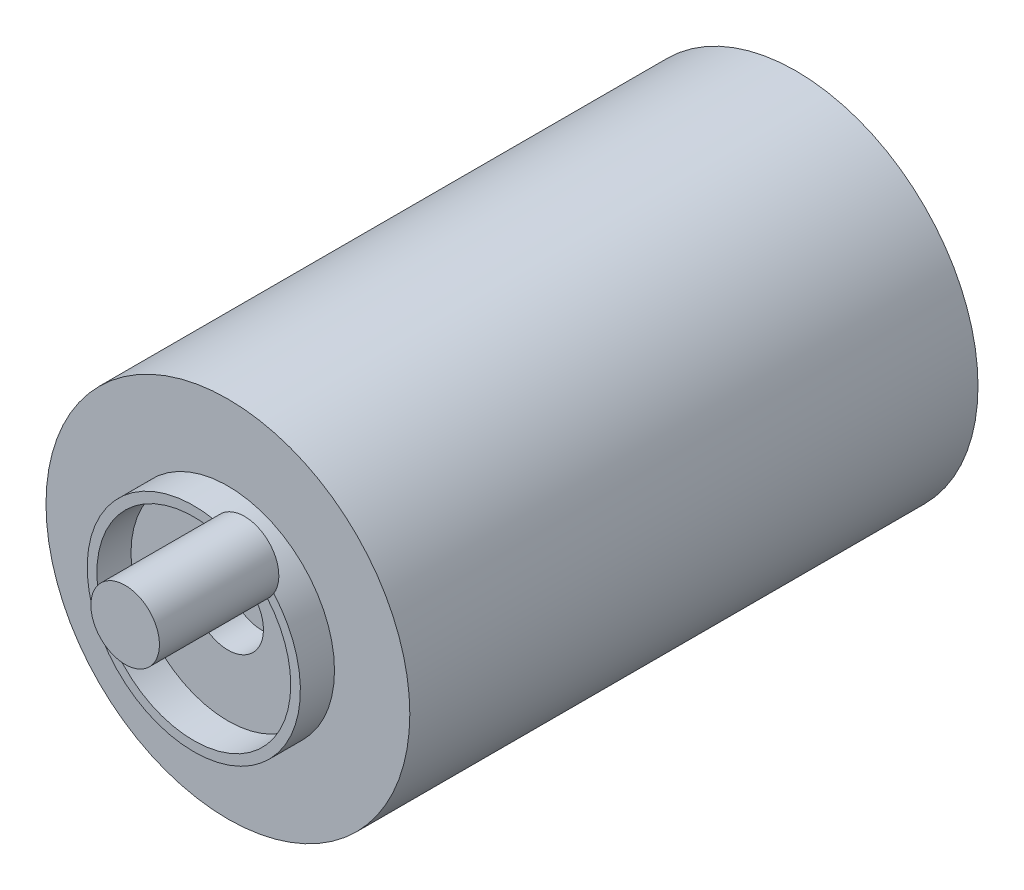
SolidWorks part; units mm, degrees
ref_plane "Front" through (0, 0, 0) normal (0, 0, 1) x (1, 0, 0)
ref_plane "Top" through (0, 0, 0) normal (0, 1, 0) x (1, 0, 0)
ref_plane "Right" through (0, 0, 0) normal (1, 0, 0) x (0, 0, -1)
sketch "Sketch1" plane through (0, 0, 0) normal (0, 0, 1) x (1, 0, 0)
  circle A0 centre (0, 0) radius 64
  point P3 (0, 0)
  dimension "D1" = 128
extrude "Boss-Extrude1" add sketch "Sketch1" along normal blind 10 and the other way blind 189.9
sketch "Sketch3" plane through (0, 0, 10) normal (0, 0, 1) x (1, 0, 0)
  circle A0 centre (0, 0) radius 37.5
  dimension "D1" = 75
extrude "Boss-Extrude2" add sketch "Sketch3" along normal blind 12 contours A0
sketch "Sketch4" plane through (0, 0, 22) normal (0, 0, 1) x (1, 0, 0)
  circle A0 centre (0, 0) radius 34.1038
  point P3 (0, 0)
extrude "Cut-Extrude1" cut sketch "Sketch4" against normal blind 12
sketch "Sketch5" plane through (0, 0, 10) normal (0, 0, 1) x (1, 0, 0)
  circle A0 centre (0, 0) radius 12.5
  dimension "D1" = 25
extrude "Cut-Extrude2" cut sketch "Sketch5" against normal blind 12 contours A0
sketch "Sketch7" plane through (0, 0, 10) normal (0, 0, 1) x (1, 0, 0)
  circle A0 centre (0, 0) radius 61.2918
sketch "Sketch11" plane through (0, 0, 22) normal (0, 0, 1) x (1, 0, 0)
  circle A0 centre (17.8483, 31.0993) radius 12.063
  point P2 (0, 0)
  point P3 (17.8483, 31.0993)
extrude "Boss-Extrude5" add sketch "Sketch11" along normal blind 42
